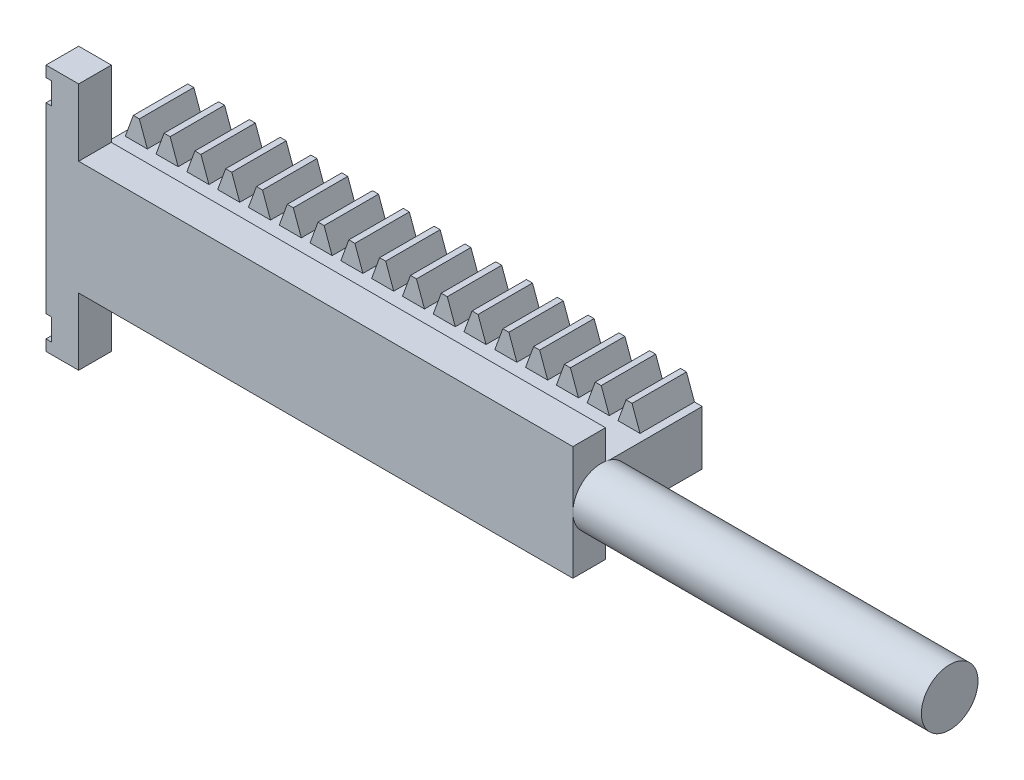
SolidWorks part; units mm, degrees
extrude "Blank" add sketch "BlankSke" against normal blind 5
sketch "BlankSke" plane through (0, 0, 0) normal (0, 0, 1) x (1, 0, 0)
  line L1 (0, 0) -> (48.375, 0)
  line L2 (0, 0) -> (0, 7)
  line L3 (0, 7) -> (48.375, 7)
  line L4 (48.375, 0) -> (48.375, 7)
  dimension "Length" = 48.375
  dimension "Blank_height" = 7
ref_plane "Plane1" through (0, 0, 0) normal (0, 0, 1) x (1, 0, 0)
ref_plane "Plane2" through (0, 0, 0) normal (0, 1, 0) x (1, 0, 0)
ref_plane "Plane3" through (0, 0, 0) normal (1, 0, 0) x (0, 0, -1)
other "Configuration Table"
sketch "HoldingSke" plane through (0, 0, 0) normal (0, 1, 0) x (1, 0, 0)
  line L0 (0, 0) -> (0.1546, 1.1003)
  line L1 (-15, 0) -> (100, 0) construction
  line L2 (0, 0) -> (-2.1039, 2.3779)
  line L3 (0, 0) -> (-11.863, 4.5341)
  line L4 (0, 0) -> (7.9495, 3.3743)
  line L5 (0, 0) -> (-23.7986, -8.8762)
  line L6 (0, 0) -> (-10.5278, -7.1032)
  line L9 (-71.009, 38.7566) -> (-14.6274, 59.2778)
  line L10 (-76.2, 3.2779) -> (-66.2, 3.2779)
  line L11 (0, 0) -> (-10, 0)
  line L12 (-76.2, 101.6) -> (-76.166, 101.6)
  line L13 (24.9733, 27.94) -> (52.9518, 28.4284)
  line L14 (24.9733, 27.94) -> (24.9743, 27.94)
  line L15 (24.9733, 27.94) -> (100.4006, 29.5858)
  circle A0 centre (0, 0) radius 19.05
  circle A1 centre (0, 0) radius 5
  circle A2 centre (0, 0) radius 12.7
  dimension "MPH" = 10
  dimension "Diameter" = 38.1
  dimension "Num_teeth" = 23
  dimension "Pitch" = 1.1111
  dimension "Show_teeth" = 998
  dimension "Thickness" = 12.7
  dimension "Ap" = 20
  dimension "Pitch_height" = 10
  dimension "Width" = 10
  dimension "Backlash" = 0.034
  dimension "Addendum_fac" = 1
  dimension "Dedendum_fac" = 1.25
  dimension "Clearance_fac" = 0.25
  dimension "Dedendum_add" = 0.001
  dimension "Length" = 60
  dimension "Module" = 0.9
sketch "TooCutSkeIll" plane through (0, 0, 0) normal (0, 0, 1) x (1, 0, 0)
  line L0 (0.2917, 6.9763) -> (-0.4535, 9.0237)
  line L1 (-0.2411, 8.875) -> (0.2411, 8.875)
  line L2 (0.4535, 9.0237) -> (-0.2917, 6.9763)
  line L3 (48.375, 7) -> (0, 7) construction
  line L4 (0, 0) -> (0, 64.897) construction
  line L5 (-13.208, 10) -> (12.954, 10) construction
  line L6 (0, 0) -> (48.375, 0) construction
  line L7 (0.8089, 10) -> (0.8089, 48.7463) construction
  line L8 (-0.8089, 10) -> (-0.8089, 48.7463) construction
  line L9 (-0.2578, 7) -> (-0.2578, 10.9254)
  line L10 (0.2578, 7) -> (0.2578, 10.9254)
  line L11 (0.2578, 10.9254) -> (-0.2578, 10.9254)
  arc A0 (0.2411, 8.875) -> (0.4535, 9.0237) centre (0.2411, 9.101) ccw
  arc A1 (-0.4535, 9.0237) -> (-0.2411, 8.875) centre (-0.2411, 9.101) ccw
  arc A2 (-0.2578, 7) -> (-0.2917, 6.9763) centre (-0.2578, 6.964) ccw
  arc A3 (0.2917, 6.9763) -> (0.2578, 7) centre (0.2578, 6.964) ccw
  dimension "Pitch_height" = 10
  dimension "Addendum_plus" = 0.9254
  dimension "Pressure_angle" = 20
  dimension "Gap_width" = 1.6177
  dimension "Dedendum" = 1.125
extrude "ToothCutIll" [suppressed] cut sketch "TooCutSkeIll" against normal through all
sketch "TooCutSkeSim" plane through (0, 0, 0) normal (0, 0, 1) x (1, 0, 0)
  line L0 (0.3994, 4.975) -> (-0.3994, 4.975)
  line L1 (1.1457, 7.0254) -> (0.3994, 4.975)
  line L2 (0, 17.4625) -> (0, 53.467) construction
  line L3 (1.1457, 7.0254) -> (-1.1457, 7.0254)
  line L6 (-1.1457, 7.0254) -> (-0.3994, 4.975)
  line L9 (-0.8089, 6.1) -> (0.8089, 6.1) construction
  line L10 (0, 0) -> (48.375, 0) construction
  line L11 (0.8089, 6.1) -> (0.8089, 53.467) construction
  line L12 (-0.8089, 6.1) -> (-0.8089, 53.467) construction
  dimension "Addendum_plus" = 0.9254
  dimension "Pitch_height" = 6.1
  dimension "Pressure_angle" = 20
  dimension "Gap_width" = 1.6177
  dimension "Dedendum" = 1.125
extrude "ToothCutSim" cut sketch "TooCutSkeSim" against normal through all
pattern_linear "TeethCuts" count 18 spacing 2.8274 along (1, 0, 0) of "ToothCutSim"
sketch "Sketch7" plane through (48.375, 0, 0) normal (1, 0, 0) x (0, 0, -1)
  line L0 (0, 4.975) -> (5, 4.975) construction
  line L1 (-6.8787, 0) -> (0, 0)
  line L2 (-6.8787, 0) -> (-6.8787, 4.975)
  line L3 (-6.8787, 4.975) -> (0, 4.975)
  line L4 (0, 0) -> (0, 4.975)
  line L5 (-6.8787, 0) -> (0, 4.975) construction
  line L6 (-6.8787, 4.975) -> (0, 0) construction
  line L7 (0, 0) -> (0, 4.975) construction
  point P0 (-3.4393, 2.4875)
  point P15 (0, 2.4875)
  point P16 (0, 2.4875)
  dimension "D1" = 6.8787
extrude "Boss-Extrude5" add sketch "Sketch7" against normal up to surface (48.375 mm away) up to face at (0, 2.4875, -2.5)
sketch "Sketch8" plane through (48.375, 0, 0) normal (1, 0, 0) x (0, 0, -1)
  line L0 (-6.8787, 4.975) -> (-6.8787, 0) construction
  circle A0 centre (-4.2787, 2.4893) radius 2.6
  point P4 (-6.8787, 2.4875)
  dimension "D1" = 5.2
extrude "Boss-Extrude6" add sketch "Sketch8" along normal blind 32
sketch "Sketch10" plane through (0, 0, 0) normal (-1, 0, 0) x (0, 0, 1)
  line L0 (-5, 4.975) -> (6.8787, 4.975) construction
  line L1 (3.8787, 4.975) -> (6.8787, 4.975)
  line L2 (3.8787, 4.975) -> (3.8787, 7.725)
  line L3 (3.8787, 7.725) -> (6.8787, 7.725)
  line L4 (6.8787, 4.975) -> (6.8787, 7.725)
  line L5 (3.8787, 4.975) -> (6.8787, 7.725) construction
  line L6 (3.8787, 7.725) -> (6.8787, 4.975) construction
  line L7 (6.8787, 4.975) -> (6.8787, 0) construction
  point P0 (5.3787, 6.35)
  dimension "D1" = 3
  dimension "D2" = 2.75
extrude "Boss-Extrude8" add sketch "Sketch10" against normal up to surface (48.375 mm away) up to face at (48.375, 0.7278, 6.3995)
ref_plane "Plane6" through (0, 2.4875, 0) normal (0, 1, 0) x (1, 0, 0)
mirror "Mirror6" about plane through (0, 2.4875, 0) normal (0, 1, 0) of "Boss-Extrude8"
sketch "Sketch11" plane through (0, -2.75, 0) normal (0, -1, 0) x (1, 0, 0)
  line L0 (48.375, 6.8787) -> (0, 6.8787) construction
  line L1 (0, 6.8787) -> (3, 6.8787)
  line L2 (0, 6.8787) -> (0, 3.8787)
  line L3 (0, 3.8787) -> (3, 3.8787)
  line L4 (3, 6.8787) -> (3, 3.8787)
  line L5 (0, 6.8787) -> (3, 3.8787) construction
  line L6 (0, 3.8787) -> (3, 6.8787) construction
  line L7 (48.375, 3.8787) -> (0, 3.8787) construction
  line L8 (0, 6.8787) -> (0, 3.8787) construction
  point P0 (1.5, 5.3787)
extrude "Boss-Extrude9" add sketch "Sketch11" along normal blind 6.15
mirror "Mirror7" about plane through (0, 2.4875, 0) normal (0, 1, 0) of "Boss-Extrude9"
sketch "Sketch12" plane through (0, 0, 0) normal (-1, 0, 0) x (0, 0, 1)
  line L0 (3.8787, -8.9) -> (3.8787, 0) construction
  line L1 (3.8787, -7.9) -> (6.8787, -7.9)
  line L2 (3.8787, -7.9) -> (3.8787, -5.9)
  line L3 (3.8787, -5.9) -> (6.8787, -5.9)
  line L4 (6.8787, -7.9) -> (6.8787, -5.9)
  line L5 (3.8787, -7.9) -> (6.8787, -5.9) construction
  line L6 (3.8787, -5.9) -> (6.8787, -7.9) construction
  line L7 (6.8787, 13.875) -> (6.8787, -8.9) construction
  line L8 (6.8787, -8.9) -> (3.8787, -8.9) construction
  point P0 (5.3787, -6.9)
  dimension "D1" = 1
  dimension "D2" = 2
extrude "Cut-Extrude1" cut sketch "Sketch12" against normal offset from surface (0.5 mm away) 2.5 up to face at (3, -5.825, 5.3787)
mirror "Mirror8" about plane through (0, 2.4875, 0) normal (0, 1, 0) of "Cut-Extrude1"
equation "' \"Module@HoldingSke\" = 6.35"
equation "' \"Num_teeth@HoldingSke\" = 12"
equation "' \"Ap@HoldingSke\" =  20"
equation "' \"Ap@HoldingSke\" = 20"
equation "' \"Width@HoldingSke\" = 0.25 * 25.4"
equation "' \"Show_teeth@HoldingSke\" = 500"
equation "' \"Backlash@HoldingSke\" = 0.009 * 25.4"
equation "' \"Addendum_fac@HoldingSke\" = 1.0"
equation "' \"Dedendum_fac@HoldingSke\" = 1.25"
equation "' \"Dedendum_add@HoldingSke\" = 0.00005 * 25.4"
equation "' \"Clearance_fac@HoldingSke\" = 0.25"
equation "' \"Pitch_height@HoldingSke\" = 1 * 25.4"
equation "' \"Length@HoldingSke\" = 4.71 * 25.4"
equation "\"Pitch@HoldingSke\" = 1 / \"Module@HoldingSke\""
equation "\"MPH@HoldingSke\" = \"Dedendum_fac@HoldingSke\" / \"Pitch@HoldingSke\" + 2 * \"Dedendum_add@HoldingSke\" + 0.002 * 25.4"
equation "\"MPH@HoldingSke\" = ((sgn( \"MPH@HoldingSke\" - \"Pitch_height@HoldingSke\")+1)*( \"MPH@HoldingSke\" - \"Pitch_height@HoldingSke\"))/2 + \"Pitch_height@HoldingSke\""
equation "\"Pressure_angle@TooCutSkeIll\" = \"Ap@HoldingSke\""
equation "\"Addendum_plus@TooCutSkeIll\" =  \"Addendum_fac@HoldingSke\"  / \"Pitch@HoldingSke\" + 0.001 *25.4"
equation "\"Dedendum@TooCutSkeIll\" = \"Dedendum_fac@HoldingSke\"  / \"Pitch@HoldingSke\""
equation "\"Pitch_height@TooCutSkeIll\" =  \"MPH@HoldingSke\""
equation "\"Gap_width@TooCutSkeIll\" = 3.14159265 / 2 / \"Pitch@HoldingSke\" + 6 * \"Backlash@HoldingSke\""
equation "\"Pressure_angle@TooCutSkeSim\" = \"Ap@HoldingSke\""
equation "\"Addendum_plus@TooCutSkeSim\" =  \"Addendum_fac@HoldingSke\"  / \"Pitch@HoldingSke\" + 0.001 * 25.4"
equation "\"Dedendum@TooCutSkeSim\" = \"Dedendum_fac@HoldingSke\"  / \"Pitch@HoldingSke\""
equation "\"Gap_width@TooCutSkeSim\" = 3.14159265 / 2 / \"Pitch@HoldingSke\" + 6 * \"Backlash@HoldingSke\""
equation "\"Root_fillet@TooCutSkeIll\" = \"Clearance_fac@HoldingSke\" / \"Pitch@HoldingSke\" + \"Dedendum_add@HoldingSke\""
equation "\"Break_rad@TooCutSkeIll\" = 0.02 / \"Pitch@HoldingSke\" * 2"
equation "\"Linear_pitch@TeethCuts\" = 3.14159265 / \"Pitch@HoldingSke\""
equation "\"Num_teeth@HoldingSke\" = int( ( \"Length@HoldingSke\" + 0 ) / (3.14159265 / \"Pitch@HoldingSke\")) + 0.9999  + 1"
equation " \"Num_teeth@TeethCuts\" = ((sgn( \"Num_teeth@TeethCuts\" - \"Num_teeth@HoldingSke\" )-1)*( \"Num_teeth@TeethCuts\" - \"Num_teeth@HoldingSke\" ))/-2+ \"Num_teeth@HoldingSke\""
equation " \"Num_teeth@TeethCuts\" = ((sgn( \"Num_teeth@TeethCuts\" - 2.0)+1)*( \"Num_teeth@TeethCuts\" - 2.0))/2 +2.0"
